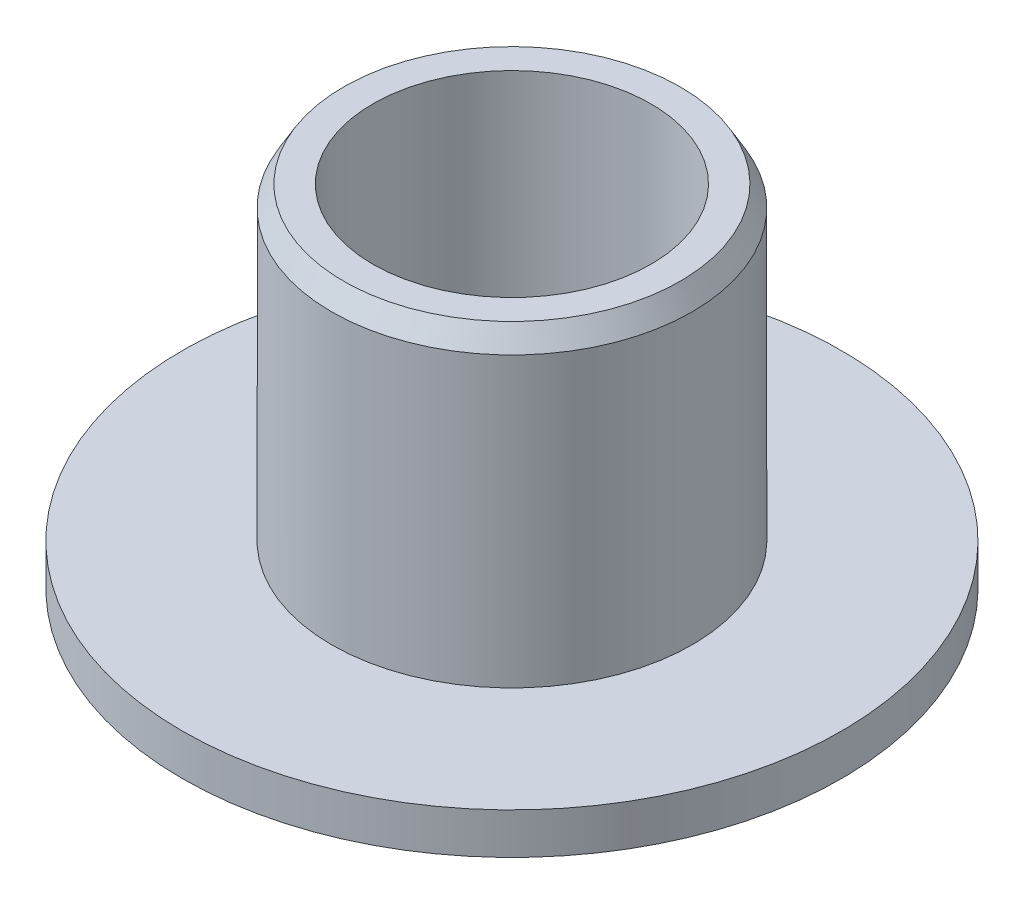
SolidWorks part; units mm, degrees
ref_plane "Front Plane" through (0, 0, 0) normal (0, 0, 1) x (1, 0, 0)
ref_plane "Top Plane" through (0, 0, 0) normal (0, 1, 0) x (1, 0, 0)
ref_plane "Right Plane" through (0, 0, 0) normal (1, 0, 0) x (0, 0, -1)
sketch "Sketch1" plane through (0, 0, 0) normal (0, 0, 1) x (1, 0, 0)
  line L0 (0, 21.623) -> (0, 0) construction
  line L1 (8.75, 2) -> (16, 2) construction
  line L2 (9, 2) -> (9, 17) construction
  line L3 (9, 17) -> (0, 17) construction
  line L4 (0, 0) -> (-1.2722, 0) construction
  line L7 (16, 2) -> (9, 2)
  line L8 (9, 2) -> (8.75, 2)
  line L11 (8.75, 17) -> (8.75, 2)
  line L12 (0, 0) -> (16, 0)
  line L13 (16, 0) -> (16, 2)
  line L15 (0, 0) -> (0, 2)
  line L16 (0, 2) -> (6.75, 2)
  line L17 (6.75, 2) -> (6.75, 17)
  line L18 (6.75, 17) -> (8.75, 17)
  dimension "D1" = 2
  dimension "D2" = 16
  dimension "D3" = 15
  dimension "D4" = 9
  dimension "D5" = 17.5
  dimension "D6" = 2
revolve "Revolve1" add sketch "Sketch1" angle 360 about L0
chamfer "Chamfer1" distance 1 angle 30 1 edges at (0, 17, 8.75)
